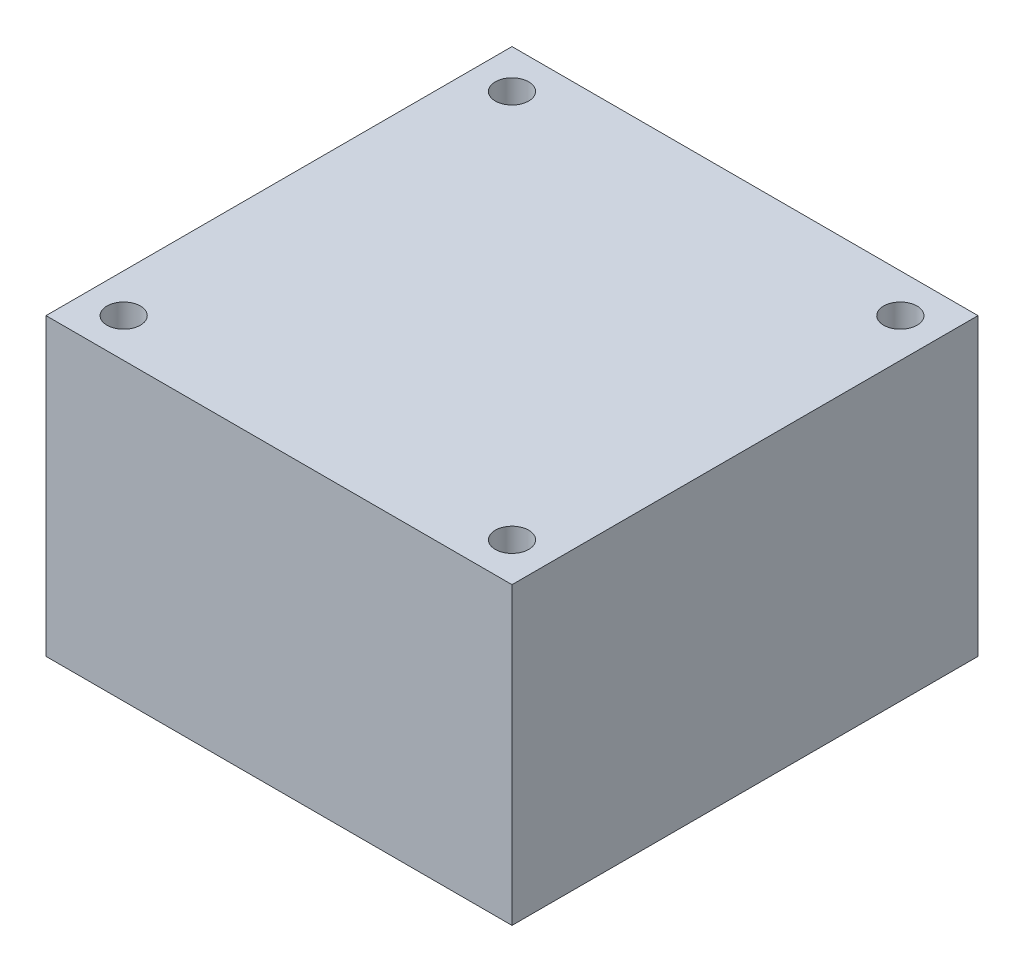
SolidWorks part; units mm, degrees
material "ABS"
ref_plane "Front Plane" through (0, 0, 0) normal (0, 0, 1) x (1, 0, 0)
ref_plane "Top Plane" through (0, 0, 0) normal (0, 1, 0) x (1, 0, 0)
ref_plane "Right Plane" through (0, 0, 0) normal (1, 0, 0) x (0, 0, -1)
sketch "Sketch1" plane through (0, 0, 0) normal (0, 1, 0) x (1, 0, 0)
  line L1 (0, 0) -> (60, 0)
  line L2 (0, 0) -> (0, 60)
  line L3 (0, 60) -> (60, 60)
  line L4 (60, 0) -> (60, 60)
  dimension "D1" = 60
  dimension "D2" = 60
extrude "Boss-Extrude1" add sketch "Sketch1" along normal blind 38
sketch "Sketch2" plane through (0, 38, 0) normal (0, 1, 0) x (1, 0, 0)
  line L4 (0, 60) -> (0, 0) construction
  line L5 (60, 60) -> (0, 60) construction
  circle A0 centre (5, 5) radius 2.15
  circle A1 centre (5, 55) radius 2.15
  circle A2 centre (55, 55) radius 2.15
  circle A3 centre (55, 5) radius 2.15
  dimension "D1" = 4.3
  dimension "D5" = 50
  dimension "D2" = 50
  dimension "D3" = 5
  dimension "D4" = 5
extrude "Cut-Extrude1" cut sketch "Sketch2" against normal through all
